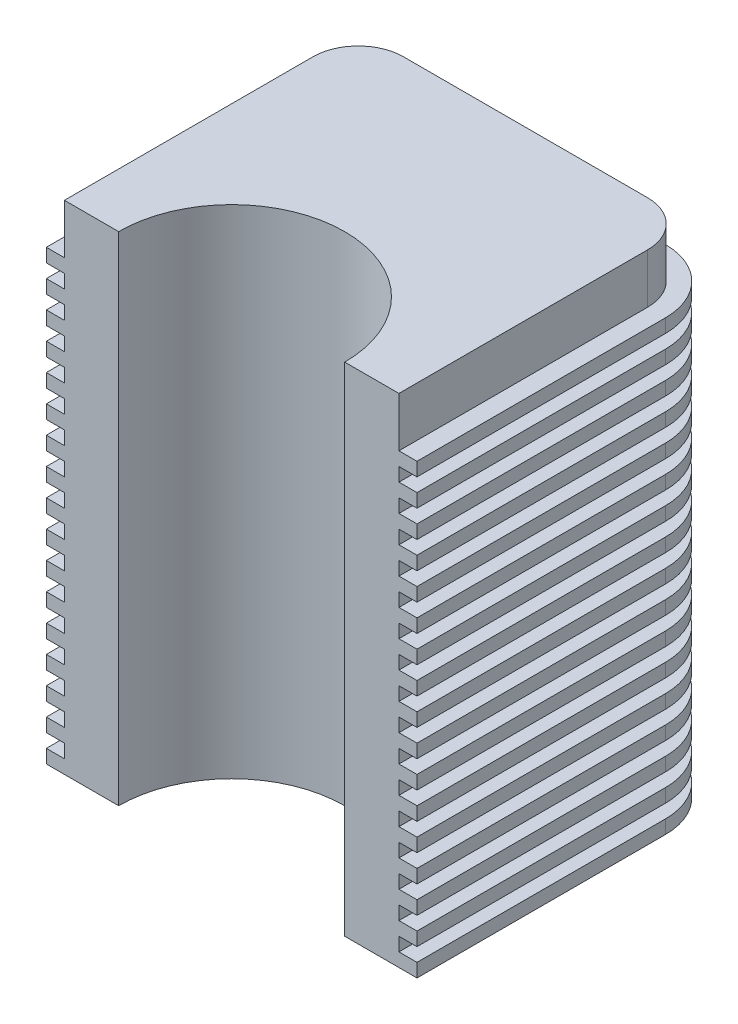
SolidWorks part; units mm, degrees
ref_plane "Front Plane" through (0, 0, 0) normal (0, 0, 1) x (1, 0, 0)
ref_plane "Top Plane" through (0, 0, 0) normal (0, 1, 0) x (1, 0, 0)
ref_plane "Right Plane" through (0, 0, 0) normal (1, 0, 0) x (0, 0, -1)
sketch "Sketch2" plane through (0, 0, 0) normal (0, 1, 0) x (1, 0, 0)
  line L0 (25, 0) -> (37, 0)
  line L1 (37, 0) -> (37, 55)
  line L2 (27, 65) -> (-27, 65)
  line L3 (0, 0) -> (0, 36.7857) construction
  line L4 (-25, 0) -> (-37, 0)
  line L5 (-37, 0) -> (-37, 55)
  arc A0 (25, 0) -> (-25, 0) centre (0, 0) ccw
  arc A1 (37, 55) -> (27, 65) centre (27, 55) ccw
  arc A2 (-37, 55) -> (-27, 65) centre (-27, 55) cw
  point P11 (0, 65)
  point P13 (37, 65)
  point P16 (-37, 65)
  dimension "D1" = 50
  dimension "D4" = 10
  dimension "D2" = 12
  dimension "D3" = 65
extrude "Boss-Extrude1" add sketch "Sketch2" along normal blind 110
sketch "Sketch4" plane through (0, 0, 0) normal (0, -1, 0) x (1, 0, 0)
  line L1 (41, -55) -> (41, 0)
  line L2 (-27, -69) -> (27, -69)
  line L3 (-41, 0) -> (-41, -55)
  line L5 (-25, 0) -> (-37, 0)
  line L6 (-37, 0) -> (-37, -55)
  line L7 (-27, -65) -> (27, -65)
  line L8 (37, -55) -> (37, 0)
  line L9 (37, 0) -> (25, 0)
  line L10 (-25, 0) -> (-37, 0)
  line L11 (-37, 0) -> (-37, -55)
  line L12 (-27, -65) -> (27, -65)
  line L13 (37, -55) -> (37, 0)
  line L14 (37, 0) -> (25, 0)
  line L15 (-37, 0) -> (-41, 0)
  line L16 (37, 0) -> (41, 0)
  line L18 (41, 4) -> (20.6155, 4) construction
  line L19 (-20.6155, 4) -> (-41, 4) construction
  line L20 (-41, 4) -> (-41, -55) construction
  line L21 (41, -55) -> (41, 4) construction
  arc A1 (27, -69) -> (41, -55) centre (27, -55) ccw
  arc A2 (-41, -55) -> (-27, -69) centre (-27, -55) ccw
  arc A3 (-25, 0) -> (25, 0) centre (0, 0) ccw
  arc A4 (-37, -55) -> (-27, -65) centre (-27, -55) ccw
  arc A5 (27, -65) -> (37, -55) centre (27, -55) ccw
  arc A6 (-25, 0) -> (25, 0) centre (0, 0) ccw
  arc A7 (-37, -55) -> (-27, -65) centre (-27, -55) ccw
  arc A8 (27, -65) -> (37, -55) centre (27, -55) ccw
  arc A9 (-20.6155, 4) -> (20.6155, 4) centre (0, 0) ccw construction
  line M19 (-37, 0) -> (-37, -55)
  arc M20 (-37, -55) -> (-27, -65) centre (-27, -55) ccw
  line M21 (-27, -65) -> (27, -65)
  arc M22 (27, -65) -> (37, -55) centre (27, -55) ccw
  line M23 (37, -55) -> (37, 0)
  dimension "D1" = 0
  dimension "D2" = 4
extrude "Boss-Extrude2" add sketch "Sketch4" against normal blind 3 contours L3 A2 L2 A1 L1 L16 L15 M23 M22 M21 M20 M19
pattern_linear "LPattern1" count 17 spacing 6 along (0, 1, 0) of "Boss-Extrude2"
sketch "Sketch5" plane through (0, 0, 0) normal (0, -1, 0) x (1, 0, 0)
  line L25 (-31.225, -7) -> (-34, -7)
  line L26 (-34, -7) -> (-34, -55)
  line L27 (-27, -62) -> (27, -62)
  line L28 (34, -55) -> (34, -7)
  line L29 (34, -7) -> (31.225, -7)
  line L30 (-31.225, -7) -> (-34, -7)
  line L31 (-34, -7) -> (-34, -55)
  line L32 (-27, -62) -> (27, -62)
  line L33 (34, -55) -> (34, -7)
  line L34 (34, -7) -> (31.225, -7)
  arc A15 (-34, -55) -> (-27, -62) centre (-27, -55) ccw
  arc A16 (27, -62) -> (34, -55) centre (27, -55) ccw
  arc A17 (-31.225, -7) -> (31.225, -7) centre (0, 0) ccw
  arc A18 (-34, -55) -> (-27, -62) centre (-27, -55) ccw
  arc A19 (27, -62) -> (34, -55) centre (27, -55) ccw
  arc A20 (-31.225, -7) -> (31.225, -7) centre (0, 0) ccw
  dimension "D2" = 7
extrude "Cut-Extrude1" cut sketch "Sketch5" against normal blind 100
